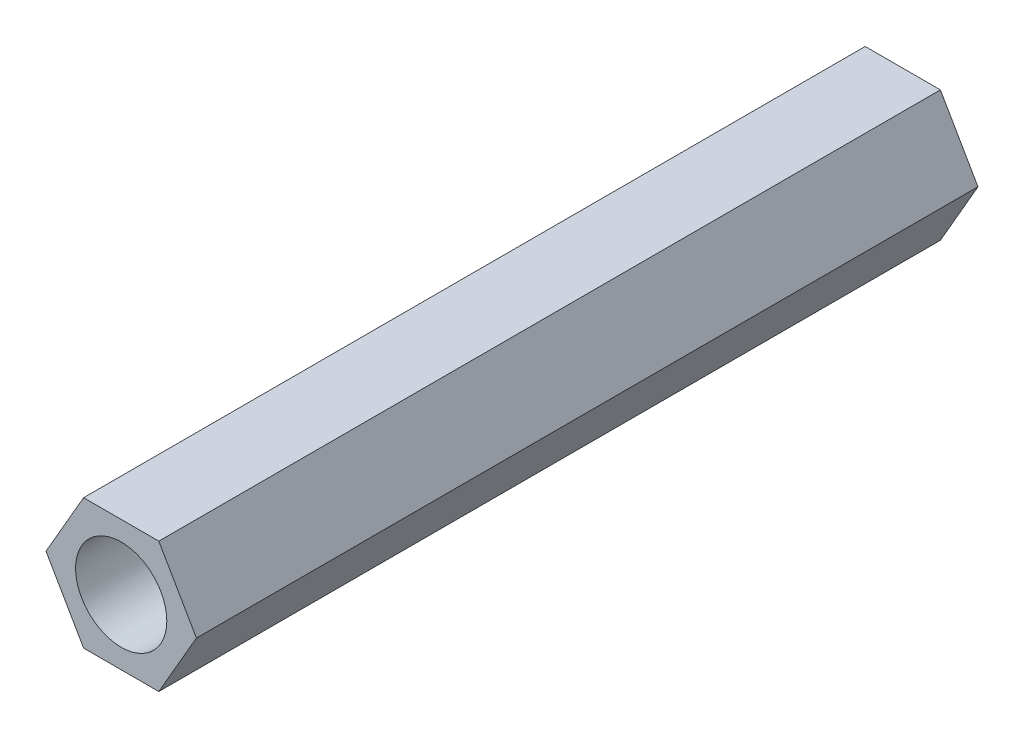
SolidWorks part; units mm, degrees
ref_plane "Alzado" through (0, 0, 0) normal (0, 0, 1) x (1, 0, 0)
ref_plane "Planta" through (0, 0, 0) normal (0, 1, 0) x (1, 0, 0)
ref_plane "Vista lateral" through (0, 0, 0) normal (1, 0, 0) x (0, 0, -1)
sketch "Croquis1" plane through (0, 0, 0) normal (0, 0, 1) x (1, 0, 0)
  line L1 (2.8868, 0) -> (1.4434, 2.5)
  line L2 (1.4434, 2.5) -> (-1.4434, 2.5)
  line L3 (-1.4434, 2.5) -> (-2.8868, 0)
  line L4 (-2.8868, 0) -> (-1.4434, -2.5)
  line L5 (-1.4434, -2.5) -> (1.4434, -2.5)
  line L6 (1.4434, -2.5) -> (2.8868, 0)
  circle A1 centre (0, 0) radius 2.5 construction
  point P1 (0, 0)
  dimension "D1" = 5
extrude "Saliente-Extruir1" add sketch "Croquis1" along normal blind 30
ref_point "Punto1"
sketch "Croquis2" plane through (0, 0, 30) normal (0, 0, 1) x (1, 0, 0)
  circle A0 centre (0, 0) radius 1.75
extrude "Cortar-Extruir1" cut sketch "Croquis2" against normal through all
